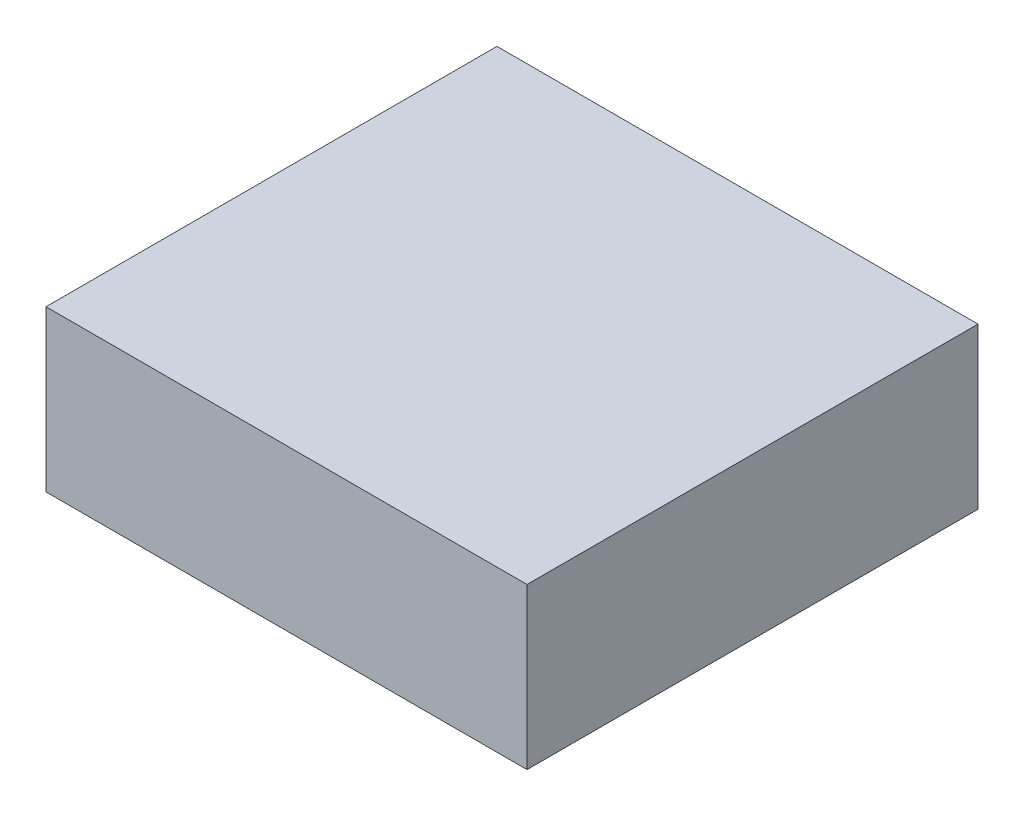
SolidWorks part; units mm, degrees
ref_plane "Спереди" through (0, 0, 0) normal (0, 0, 1) x (1, 0, 0)
ref_plane "Сверху" through (0, 0, 0) normal (0, 1, 0) x (1, 0, 0)
ref_plane "Справа" through (0, 0, 0) normal (1, 0, 0) x (0, 0, -1)
sketch "Эскиз1" plane through (0, 0, 0) normal (0, 1, 0) x (1, 0, 0)
  line L1 (48, -45) -> (-48, -45)
  line L2 (48, -45) -> (48, 45)
  line L3 (48, 45) -> (-48, 45)
  line L4 (-48, -45) -> (-48, 45)
  line L5 (48, -45) -> (-48, 45) construction
  line L6 (48, 45) -> (-48, -45) construction
  point P0 (0, 0)
  dimension "D1" = 96
  dimension "D2" = 90
extrude "Бобышка-Вытянуть1" add sketch "Эскиз1" along normal blind 32
